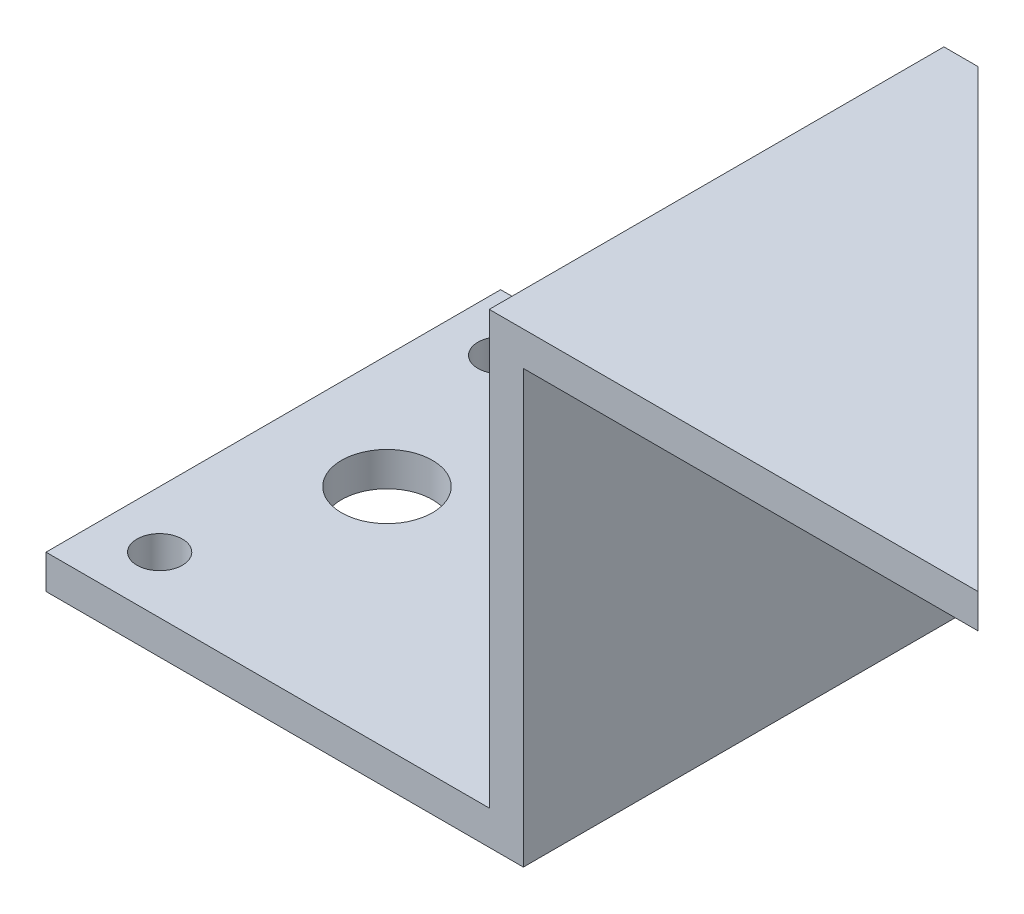
SolidWorks part; units mm, degrees
ref_plane "Front Plane" through (0, 0, 0) normal (0, 0, 1) x (1, 0, 0)
ref_plane "Top Plane" through (0, 0, 0) normal (0, 1, 0) x (1, 0, 0)
ref_plane "Right Plane" through (0, 0, 0) normal (1, 0, 0) x (0, 0, -1)
sketch "Sketch1" plane through (0, 0, 0) normal (0, 1, 0) x (1, 0, 0)
  line L1 (-21, 20) -> (21, 20)
  line L2 (-21, 20) -> (-21, -20)
  line L3 (-21, -20) -> (21, -20)
  line L4 (21, 20) -> (21, -20)
  line L5 (-21, 20) -> (21, -20) construction
  line L6 (-21, -20) -> (21, 20) construction
  circle A0 centre (-16, 15) radius 2
  circle A1 centre (-16, -15) radius 2
  circle A2 centre (-11, 0) radius 4
  point P0 (0, 0)
  dimension "D3" = 5
  dimension "D4" = 5
  dimension "D5" = 5
  dimension "D6" = 5
  dimension "D7" = 4
  dimension "D8" = 4
  dimension "D9" = 8
  dimension "D10" = 10
  dimension "D11" = 20
  dimension "D1" = 42
  dimension "D2" = 40
extrude "Boss-Extrude1" add sketch "Sketch1" along normal blind 3
sketch "Sketch2" plane through (0, 3, 0) normal (0, 1, 0) x (1, 0, 0)
  line L0 (-21, -20) -> (21, -20) construction
  line L1 (21, 20) -> (18, 20)
  line L2 (21, 20) -> (21, -20)
  line L3 (21, -20) -> (18, -20)
  line L4 (18, 20) -> (18, -20)
  dimension "D1" = 3
extrude "Boss-Extrude2" add sketch "Sketch2" along normal blind 38
sketch "Sketch3" plane through (21, 0, 0) normal (1, 0, 0) x (0, 0, -1)
  line L0 (20, 41) -> (20, 0) construction
  line L1 (-20, 41) -> (20, 41)
  line L2 (-20, 41) -> (-20, 38)
  line L3 (-20, 38) -> (20, 38)
  line L4 (20, 41) -> (20, 38)
  dimension "D1" = 3
extrude "Boss-Extrude3" add sketch "Sketch3" along normal blind 40
sketch "Sketch8" plane through (0, 38, 0) normal (0, -1, 0) x (1, 0, 0)
  line L0 (21, -20) -> (61, 20)
  line L2 (61, 20) -> (61, -20)
  line L5 (61, -20) -> (21, -20)
extrude "Cut-Extrude3" cut sketch "Sketch8" against normal blind 3
